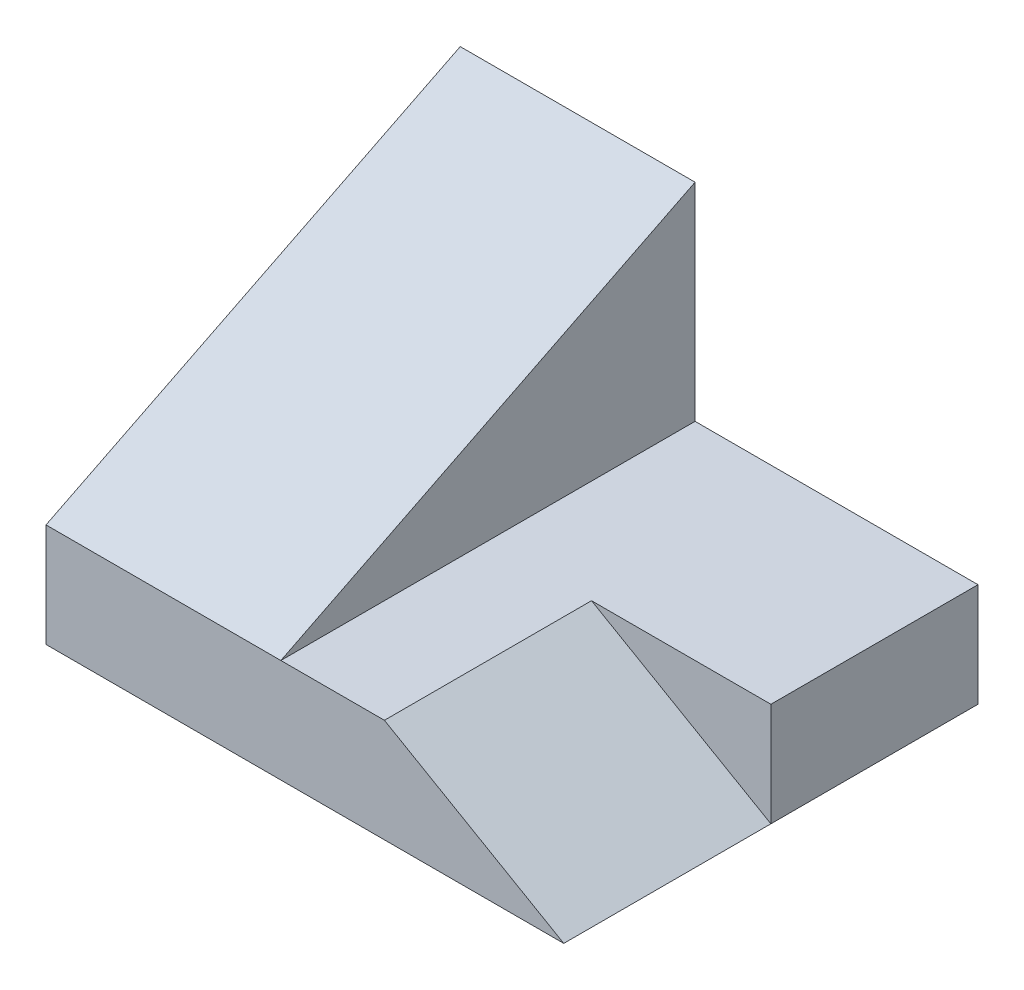
SolidWorks part; units mm, degrees
ref_plane "Front Plane" through (0, 0, 0) normal (0, 0, 1) x (1, 0, 0)
ref_plane "Top Plane" through (0, 0, 0) normal (0, 1, 0) x (1, 0, 0)
ref_plane "Right Plane" through (0, 0, 0) normal (1, 0, 0) x (0, 0, -1)
sketch "Sketch2" plane through (0, 0, 0) normal (0, 1, 0) x (1, 0, 0)
  line L0 (0, 0) -> (50, 0)
  line L1 (50, 0) -> (50, 40)
  line L2 (50, 40) -> (0, 40)
  line L3 (0, 40) -> (0, 0)
  dimension "D1" = 50
  dimension "D2" = 40
extrude "Boss-Extrude1" add sketch "Sketch2" along normal blind 10
sketch "Sketch4" plane through (0, 0, 0) normal (0, 0, 1) x (1, 0, 0)
  line L0 (32.6795, 10) -> (50, 0)
  line L1 (0, 10) -> (50, 10) construction
  line L2 (50, 0) -> (50, 10)
  line L3 (50, 10) -> (50, 0) construction
  line L4 (50, 10) -> (32.6795, 10)
  dimension "D1" = 20
extrude "Cut-Extrude4" cut sketch "Sketch4" against normal blind 20
sketch "Sketch6" plane through (0, 10, 0) normal (0, 1, 0) x (1, 0, 0)
  line L0 (22.6795, 40) -> (22.6795, 0)
  line L1 (50, 40) -> (0, 40) construction
  line L2 (0, 0) -> (32.6795, 0) construction
  line L3 (22.6795, 0) -> (0, 0)
  line L4 (0, 0) -> (0, 40)
  line L5 (0, 40) -> (22.6795, 40)
  line L6 (32.6795, 20) -> (32.6795, 0) construction
  dimension "D1" = 10
extrude "Boss-Extrude3" add sketch "Sketch6" along normal blind 20
sketch "Sketch8" plane through (22.6795, 0, 0) normal (1, 0, 0) x (0, 0, -1)
  line L0 (40, 30) -> (0, 10)
  line L1 (0, 10) -> (0, 30)
  line L2 (0, 30) -> (40, 30)
extrude "Cut-Extrude9" cut sketch "Sketch8" against normal blind 30
